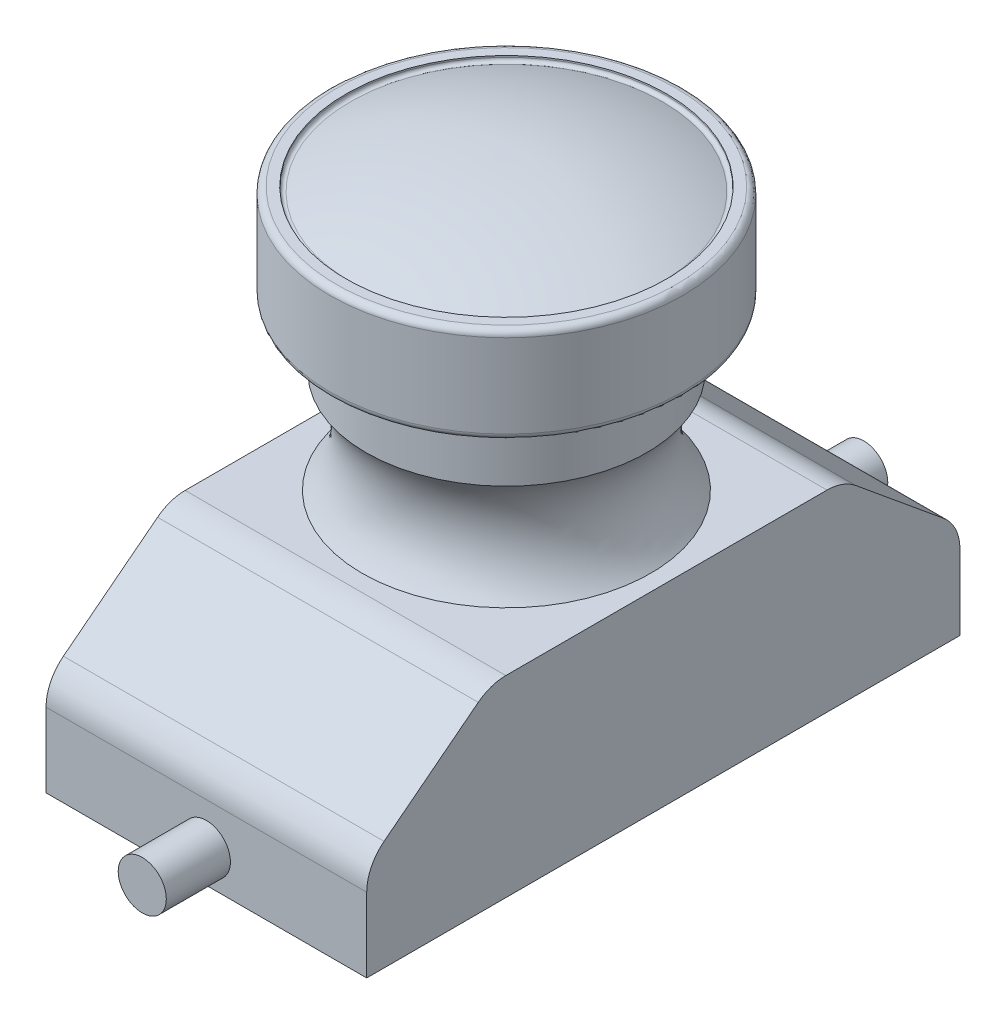
SolidWorks part; units mm, degrees
ref_plane "Front Plane" through (0, 0, 0) normal (0, 0, 1) x (1, 0, 0)
ref_plane "Top Plane" through (0, 0, 0) normal (0, 1, 0) x (1, 0, 0)
ref_plane "Right Plane" through (0, 0, 0) normal (1, 0, 0) x (0, 0, -1)
sketch "Sketch1" plane through (0, 0, 0) normal (1, 0, 0) x (0, 0, -1)
  line L0 (-9.3642, -0.0064) -> (9.1358, -0.0064)
  line L1 (-9.3642, -0.0064) -> (-9.3642, 2.9936)
  line L2 (-9.3642, 2.9936) -> (-5.5076, 5.9936)
  line L3 (-5.5076, 5.9936) -> (5.4924, 5.9936)
  line L4 (5.4924, 5.9936) -> (9.1358, 2.9936)
  line L5 (9.1358, 2.9936) -> (9.1358, -0.0064)
  line L6 (0, 0) -> (0, 8.3771) construction
  point P4 (0, 0)
  dimension "D1" = 18.5
  dimension "D2" = 3
  dimension "D3" = 3
  dimension "D4" = 11
  dimension "D5" = 3
extrude "Boss-Extrude1" add sketch "Sketch1" along normal mid plane 10
sketch "Sketch3" plane through (0, 0, 0) normal (1, 0, 0) x (0, 0, -1)
  line L0 (-0.0076, 5.9936) -> (-0.0076, 13.9936)
  line L1 (5.4924, 5.9936) -> (-5.5076, 5.9936) construction
  line L2 (-0.0076, 13.9936) -> (-5.0076, 13.9936)
  line L3 (-5.0076, 13.9936) -> (-5.0076, 14.1936)
  line L4 (-5.0076, 14.1936) -> (-5.5076, 14.1936)
  line L5 (-5.5076, 14.1936) -> (-5.5076, 11.1936)
  line L6 (-5.5076, 11.1936) -> (-4.3884, 11.1936)
  line L7 (-4.3884, 11.1936) -> (-4.3884, 9.1936)
  line L8 (-0.0076, 5.9936) -> (-4.5076, 5.9936)
  arc A0 (-4.3884, 9.1936) -> (-4.5076, 5.9936) centre (-6.3667, 7.6651) cw
  dimension "D2" = 2.5
  dimension "D1" = 4.5
  dimension "D3" = 8
  dimension "D4" = 0.2
  dimension "D5" = 3
  dimension "D6" = 0.5
  dimension "D7" = 2
  dimension "D8" = 5
revolve "Revolve1" add sketch "Sketch3" angle 360 about L0
sketch "Sketch4" plane through (0, 0, 0) normal (1, 0, 0) x (0, 0, -1)
  line L0 (-0.0076, 14.1936) -> (-0.0076, 14.9936)
  line L1 (4.9924, 14.1936) -> (-5.0076, 14.1936) construction
  line L2 (-0.0076, 14.1936) -> (-0.0076, 13.9936)
  line L3 (-0.0076, 13.9936) -> (4.9924, 13.9936)
  arc A0 (4.9924, 13.9936) -> (-0.0076, 14.9936) centre (0.1928, 2.9953) ccw
  dimension "D4" = 12
  dimension "D1" = 0.8
  dimension "D2" = 0.2
  dimension "D3" = 5
revolve "Revolve2" add sketch "Sketch4" angle 360 about L0
fillet "Fillet2" radius 0.2 2 edges at (0, 11.1936, -5.4924) (0, 14.1936, -5.4924)
fillet "Fillet3" radius 0.1 1 edges at (0, 13.9936, -4.9924)
fillet "Fillet4" radius 1.4 4 edges at (0, 2.9936, -9.1358) (0, 5.9936, -5.4924) (0, 2.9936, 9.3642) (0, 5.9936, 5.5076)
sketch "Sketch5" plane through (0, 0, 9.3642) normal (0, 0, 1) x (1, 0, 0)
  circle A0 centre (0, 1) radius 0.75
  dimension "D1" = 1.5
  dimension "D2" = 1
extrude "Boss-Extrude2" add sketch "Sketch5" along normal blind 2
sketch "Sketch6" plane through (0, 0, -9.1358) normal (0, 0, -1) x (-1, 0, 0)
  circle A0 centre (0, 1) radius 0.75
  dimension "D1" = 1.5
  dimension "D2" = 1
extrude "Boss-Extrude3" add sketch "Sketch6" along normal blind 2
mirror "Mirror4" about plane through (0, 0, 0) normal (0, 0, 1) of "Boss-Extrude3"
